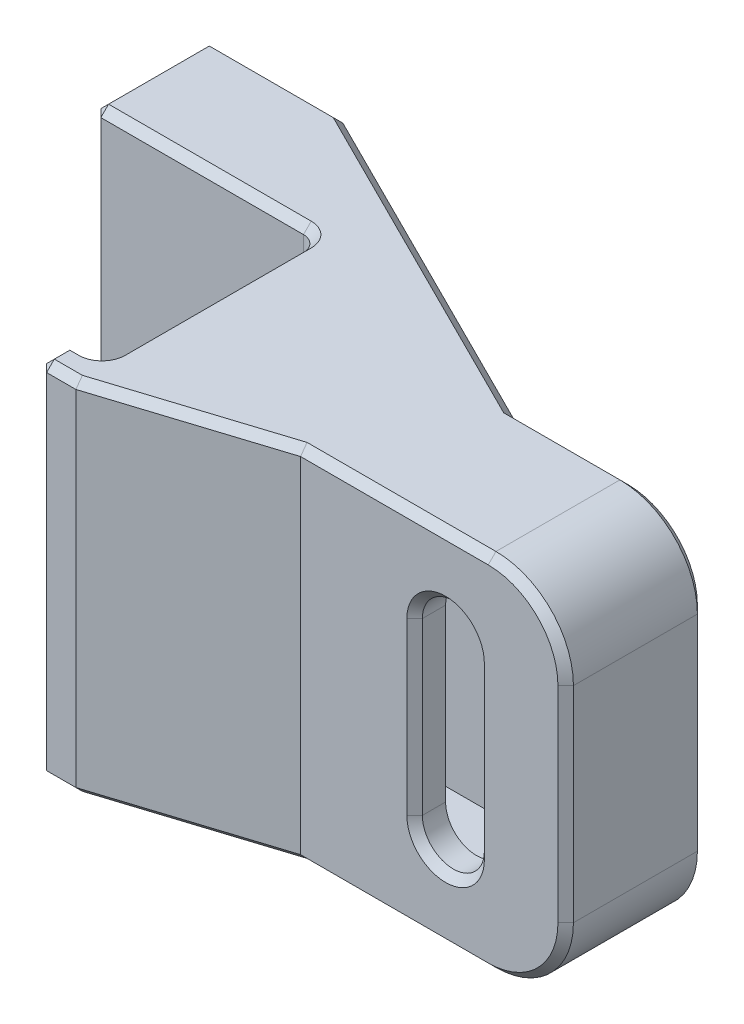
SolidWorks part; units mm, degrees
material "PET"
ref_plane "Front Plane" through (0, 0, 0) normal (0, 0, 1) x (1, 0, 0)
ref_plane "Top Plane" through (0, 0, 0) normal (0, 1, 0) x (1, 0, 0)
ref_plane "Right Plane" through (0, 0, 0) normal (1, 0, 0) x (0, 0, -1)
sketch "Reference" plane through (0, 0, 0) normal (0, 1, 0) x (1, 0, 0)
  line L0 (0, 0) -> (4, 0) construction
  line L1 (4, 0) -> (26, 7) construction
  line L2 (26, 7) -> (56, 7) construction
  line L3 (56, 7) -> (56, 15) construction
  line L4 (56, 15) -> (26, 15) construction
  line L5 (26, 15) -> (4, 26) construction
  line L6 (4, 26) -> (0, 26) construction
  dimension "D1" = 4
  dimension "D2" = 26
  dimension "D3" = 30
  dimension "D4" = 8
  dimension "D5" = 15
  dimension "D6" = 11
sketch "Sketch2" plane through (0, 0, 0) normal (0, 1, 0) x (1, 0, 0)
  line L0 (61, 20) -> (26.2361, 20) construction
  line L1 (36.2361, 20) -> (-7.7639, 42)
  line L2 (-25, 42) -> (-25, 27)
  line L44 (0, -5) -> (4.7763, -5)
  line L45 (4.7763, -5) -> (26.7763, 2)
  line L46 (26.7763, 2) -> (61, 2)
  line L47 (61, 2) -> (61, 20)
  line L48 (61, 20) -> (36.2361, 20)
  line L49 (0, -5) -> (0, -1)
  line L50 (-25, 42) -> (-7.7639, 42)
  line L51 (4.2361, 27) -> (0, 27)
  line L52 (26.2361, 16) -> (4.2361, 27)
  line L53 (57, 16) -> (26.2361, 16)
  line L54 (57, 6) -> (57, 16)
  line L55 (26.1553, 6) -> (57, 6)
  line L56 (4.1553, -1) -> (26.1553, 6)
  line L57 (0, -1) -> (4.1553, -1)
  line L58 (4.2361, 27) -> (-25, 27)
  line L59 (26.2361, 16) -> (4.2361, 27)
  line L60 (57, 16) -> (26.2361, 16)
  line L61 (57, 6) -> (57, 16)
  line L62 (26.1553, 6) -> (57, 6)
  line L63 (4.1553, -1) -> (26.1553, 6)
  line L64 (0, -1) -> (4.1553, -1)
  dimension "D3" = 12
  dimension "D4" = 25
  dimension "D5" = 15
  dimension "D1" = 1
  dimension "D2" = 4
extrude "Create internal geometry" add sketch "Sketch2" along normal blind 38.5
sketch "Sketch4" plane through (0, 0, -2) normal (0, 0, 1) x (1, 0, 0)
  line L0 (45.5, 30.25) -> (45.5, 8.25) construction
  line L1 (49.5, 30.25) -> (49.5, 8.25)
  line L2 (41.5, 30.25) -> (41.5, 8.25)
  line L3 (61, 19.25) -> (-25, 19.25) construction
  line L4 (61, 38.5) -> (61, 0) construction
  line L5 (-25, 38.5) -> (-25, 0) construction
  line L6 (61, 38.5) -> (61, 0) construction
  arc A0 (49.5, 30.25) -> (41.5, 30.25) centre (45.5, 30.25) ccw
  arc A1 (41.5, 8.25) -> (49.5, 8.25) centre (45.5, 8.25) ccw
  point P2 (45.5, 19.25)
  dimension "D1" = 8
  dimension "D2" = 22
  dimension "D3" = 11.5
extrude "Cut shackle hole" cut sketch "Sketch4" against normal through all
ref_plane "Mid plane" through (0, 19.25, 0) normal (0, 1, 0) x (1, 0, 0)
sketch "Sketch3" plane through (0, 38.5, 0) normal (0, 1, 0) x (1, 0, 0)
  line L0 (-25, 27) -> (4.2361, 27) construction
  line L1 (-25, 42) -> (-25, 27) construction
  line L2 (-7.7639, 42) -> (-25, 42) construction
  line L3 (36.2361, 20) -> (-7.7639, 42) construction
  line L4 (61, 20) -> (36.2361, 20) construction
  line L5 (61, 2) -> (61, 20) construction
  line L6 (26.7763, 2) -> (61, 2) construction
  line L7 (4.7763, -5) -> (26.7763, 2) construction
  line L8 (0, -5) -> (4.7763, -5) construction
  line L9 (4.1553, -1) -> (0, -1) construction
  line L10 (0, -1) -> (0, -5) construction
  line L11 (-25, 27) -> (2.1553, 27)
  line L12 (-25, 42) -> (-25, 27)
  line L13 (-7.7639, 42) -> (-25, 42)
  line L14 (36.2361, 20) -> (-7.7639, 42)
  line L15 (61, 20) -> (36.2361, 20)
  line L16 (61, 2) -> (61, 20)
  line L17 (26.7763, 2) -> (61, 2)
  line L18 (4.7763, -5) -> (26.7763, 2)
  line L19 (0, -5) -> (4.7763, -5)
  line L20 (2.1553, -1) -> (0, -1)
  line L21 (0, -1) -> (0, -5)
  line L22 (4.1553, 25) -> (4.1553, 1)
  arc A0 (4.1553, 1) -> (2.1553, -1) centre (2.1553, 1) cw
  arc A1 (4.1553, 25) -> (2.1553, 27) centre (2.1553, 25) ccw
  dimension "D1" = 2
extrude "Cap top end" add sketch "Sketch3" along normal blind 4
mirror "Mirror top cap to bottom" about plane through (0, 19.25, 0) normal (0, 1, 0) of "Cap top end"
fillet "Round corners" radius 10 4 edges at (61, 42.5, -11) (61, -4, -11) (57, 38.5, -11) (57, 0, -11)
chamfer "Unnecessary chamfers" distance 1 angle 45 44 edges at (61, 19.25, -2) (61, 19.25, -20) (58.0711, -1.0711, -20) (58.0711, -1.0711, -2) (58.0711, 39.5711, -2) (58.0711, 39.5711, -20) (43.618, -4, -20) (14.2361, -4, -31) (-16.382, -4, -42) (-25, -4, -34.5) (-11.4224, -4, -27) (3.5695, -4, -26.4142) (4.1553, -4, -13) (3.5695, -4, 0.4142) (1.0776, -4, 1) (0, -4, 3) (38.8881, -4, -2) (15.7763, -4, 1.5) (2.3881, -4, 5) (38.8881, 42.5, -2) (15.7763, 42.5, 1.5) (2.3881, 42.5, 5) (0, 19.25, 5) (0, 42.5, 3) (0, 19.25, 1) (1.0776, 42.5, 1) (3.5695, 42.5, 0.4142) (4.1553, 42.5, -13) (3.5695, 42.5, -26.4142) (-11.4224, 42.5, -27) (-25, 19.25, -27) (-25, 42.5, -34.5) (43.618, 42.5, -20) (14.2361, 42.5, -31) (-16.382, 42.5, -42) (-25, 19.25, -42) (49.5, 19.25, -20) (45.5, 34.25, -20) (45.5, 4.25, -20) (41.5, 19.25, -20) (45.5, 34.25, -2) (41.5, 19.25, -2) (49.5, 19.25, -2) (45.5, 4.25, -2)
